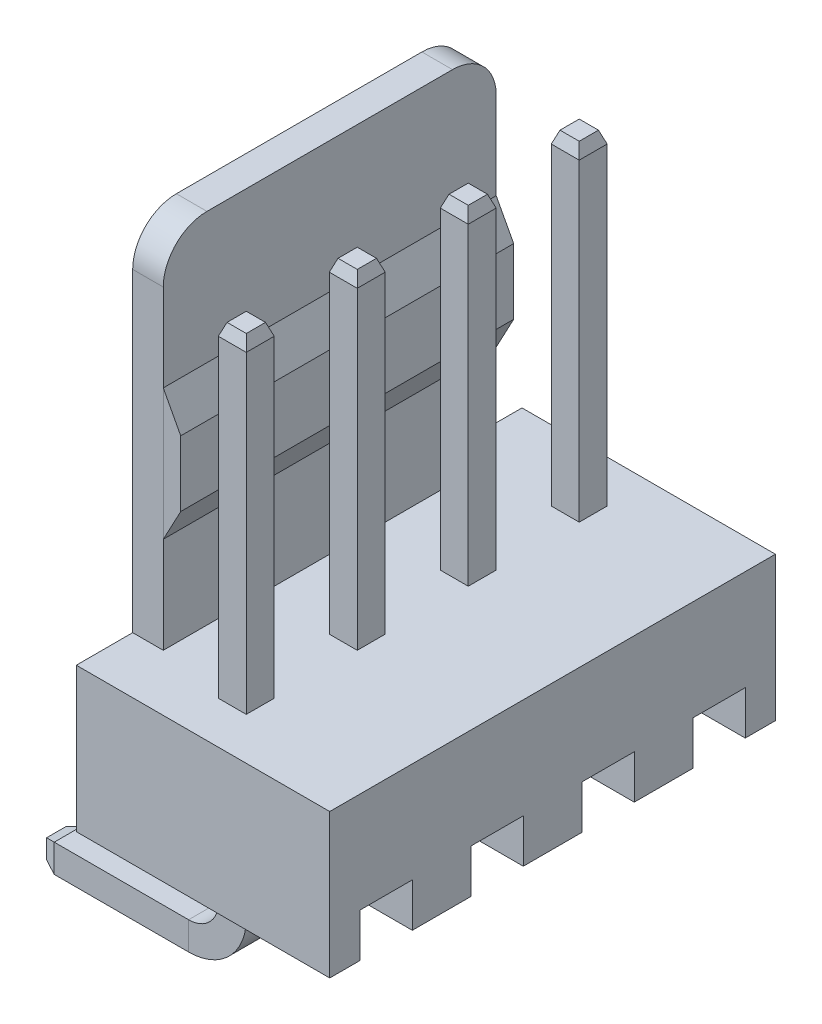
SolidWorks part; units mm, degrees
ref_plane "Спереди" through (0, 0, 0) normal (0, 0, 1) x (1, 0, 0)
ref_plane "Сверху" through (0, 0, 0) normal (0, 1, 0) x (1, 0, 0)
ref_plane "Справа" through (0, 0, 0) normal (1, 0, 0) x (0, 0, -1)
sketch "Эскиз1" plane through (0, 0, 0) normal (1, 0, 0) x (0, 0, -1)
  line L1 (-0.95, 0.32) -> (-1.59, 0.32)
  line L2 (-0.95, 0.32) -> (-0.95, -0.32)
  line L3 (-0.95, -0.32) -> (-1.59, -0.32)
  line L4 (-1.59, 0.32) -> (-1.59, -0.32)
  line L5 (-0.95, 0.32) -> (-1.59, -0.32) construction
  line L6 (-0.95, -0.32) -> (-1.59, 0.32) construction
  point P0 (-1.27, 0)
  point P5 (0, 0)
  dimension "D1" = 0.64
  dimension "D2" = 1.27
sketch3d "Трехмерный эскиз1"
  line L0 (0, 0, 1.27) -> (-1.75, 0, 1.27)
  line L1 (0, 0, 1.27) -> (1.6, 0, 1.27)
  line L2 (2.6, 1, 1.27) -> (2.6, 12.5, 1.27)
  arc A0 (1.6, 0, 1.27) -> (2.6, 1, 1.27) centre (1.6, 1, 1.27) ccw
  point P7 (2.6, 0, 1.27)
  point P8 (1.6, 1, 2.27)
  dimension "D4" = 1
  dimension "D1" = 12.5
  dimension "D2" = 2.6
  dimension "D3" = 1.75
sweep "По траектории1" add profiles "Эскиз1" path "Трехмерный эскиз1"
chamfer "Фаска1" distance 0.1 angle 70 4 edges at (2.28, 12.5, 1.27) (2.6, 12.5, 0.95) (2.92, 12.5, 1.27) (2.6, 12.5, 1.59)
chamfer "Фаска2" distance 0.1 angle 70 4 edges at (-1.75, -0.32, 1.27) (-1.75, 0, 0.95) (-1.75, 0.32, 1.27) (-1.75, 0, 1.59)
pattern_linear "Линейный массив2" count 3 spacing 2.54 along (0, 0, -1) of bodies 103
pattern_linear "Линейный массив3" count 2 spacing 2.54 along (0, 0, 1) of "По траектории1"
sketch "Эскиз2" plane through (0, 0, 0) normal (1, 0, 0) x (0, 0, -1)
  line L0 (1.87, 0.75) -> (1.87, 2.75)
  line L1 (-5.1, 1.75) -> (5.1, 1.75)
  line L2 (-5.1, 1.75) -> (-5.1, 5.05)
  line L3 (-5.1, 5.05) -> (5.1, 5.05)
  line L4 (5.1, 1.75) -> (5.1, 5.05)
  line L5 (-5.1, 1.75) -> (5.1, 5.05) construction
  line L6 (-5.1, 5.05) -> (5.1, 1.75) construction
  line L7 (4.41, 0.75) -> (3.21, 0.75)
  line L8 (4.41, 0.75) -> (4.41, 2.75)
  line L9 (4.41, 2.75) -> (3.21, 2.75)
  line L10 (3.21, 0.75) -> (3.21, 2.75)
  line L11 (4.41, 0.75) -> (3.21, 2.75) construction
  line L12 (4.41, 2.75) -> (3.21, 0.75) construction
  line L17 (1.87, 0.75) -> (0.67, 0.75)
  line L18 (0.67, 0.75) -> (0.67, 2.75)
  line L23 (1.87, 2.75) -> (0.67, 2.75)
  line L24 (-0.67, 0.75) -> (-0.67, 2.75)
  line L29 (-0.67, 0.75) -> (-1.87, 0.75)
  line L30 (-1.87, 0.75) -> (-1.87, 2.75)
  line L31 (-0.67, 2.75) -> (-1.87, 2.75)
  line L32 (-3.21, 0.75) -> (-3.21, 2.75)
  line L33 (-3.21, 0.75) -> (-4.41, 0.75)
  line L34 (-4.41, 0.75) -> (-4.41, 2.75)
  line L35 (-3.21, 2.75) -> (-4.41, 2.75)
  point P0 (0, 3.4)
  point P6 (3.81, 1.75)
  dimension "D1" = 3.3
  dimension "D2" = 10.2
  dimension "D3" = 1.75
  dimension "D4" = 3.81
  dimension "D5" = 1.2
  dimension "D6" = 2
  dimension "D7" = 4
extrude "Бобышка-Вытянуть1" add sketch "Эскиз2" along normal blind 5.8 separate body contours L35 L32 L1 L30 L31 L24 L18 L23 L0 L10 L9 L8 L4 L3 L2 L34
sketch "Эскиз3" plane through (0, 0, 0) normal (-1, 0, 0) x (0, 0, 1)
  line L0 (5.1, 5.05) -> (-5.1, 5.05) construction
  line L1 (-3.81, 5.05) -> (3.81, 5.05)
  line L2 (-3.81, 5.05) -> (-3.81, 12.25)
  line L3 (-2.81, 13.25) -> (2.81, 13.25)
  line L4 (3.81, 5.05) -> (3.81, 12.25)
  line L5 (-4.41, 1.75) -> (-5.1, 1.75) construction
  arc A0 (2.81, 13.25) -> (3.81, 12.25) centre (2.81, 12.25) cw
  arc A1 (-3.81, 12.25) -> (-2.81, 13.25) centre (-2.81, 12.25) cw
  point P6 (0, 5.05)
  point P10 (0, 0)
  point P13 (3.81, 13.25)
  point P16 (-3.81, 13.25)
  dimension "D3" = 1
  dimension "D1" = 7.62
  dimension "D2" = 11.5
extrude "Бобышка-Вытянуть2" add sketch "Эскиз3" against normal blind 0.7 separate body contours A1 L3 A0 L4 L1 L2
sketch "Эскиз4" plane through (0, 0, -3.81) normal (0, 0, -1) x (-1, 0, 0)
  line L0 (-0.7, 7.2511) -> (-1.1, 8.0011)
  line L1 (-0.7, 5.05) -> (-0.7, 12.25) construction
  line L2 (-1.1, 8.0011) -> (-1.1, 9.5011)
  line L3 (-1.1, 9.5011) -> (-0.7, 10.2511)
  line L4 (-0.7, 10.2511) -> (-0.7, 7.2511)
  line L5 (-0.7, 8.7511) -> (-1.6837, 8.7511) construction
  point P8 (0, 0)
  point P9 (0, 0)
  point P10 (0, 0)
  dimension "D1" = 0.4
  dimension "D2" = 1.5
  dimension "D3" = 3
extrude "Бобышка-Вытянуть3" add sketch "Эскиз4" against normal up to surface (7.62 mm away) separate body up to face at (0.35, 8.65, 3.81)
